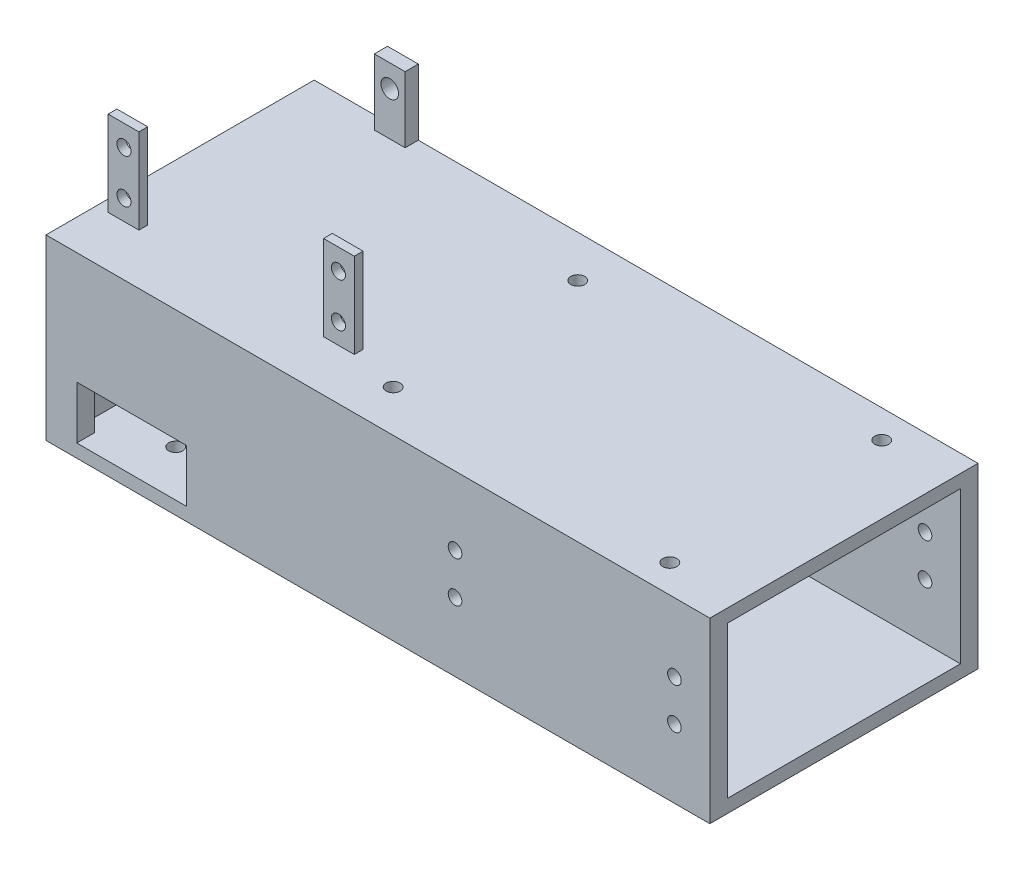
SolidWorks part; units mm, degrees
ref_plane "정면" through (0, 0, 0) normal (0, 0, 1) x (1, 0, 0)
ref_plane "윗면" through (0, 0, 0) normal (0, 1, 0) x (1, 0, 0)
ref_plane "우측면" through (0, 0, 0) normal (1, 0, 0) x (0, 0, -1)
sketch "Sketch1" plane through (0, 0, 0) normal (0, 1, 0) x (1, 0, 0)
  line L0 (-75.5, 30.5) -> (75.5, 30.5)
  line L1 (-71.5, 26.5) -> (71.5, 26.5)
  line L2 (-71.5, 26.5) -> (-71.5, -26.5)
  line L3 (-71.5, -26.5) -> (71.5, -26.5)
  line L4 (71.5, 26.5) -> (71.5, -26.5)
  line L5 (-71.5, 26.5) -> (71.5, -26.5) construction
  line L6 (-71.5, -26.5) -> (71.5, 26.5) construction
  line L7 (75.5, 30.5) -> (75.5, -30.5)
  line L8 (-75.5, -30.5) -> (75.5, -30.5)
  line L9 (-75.5, 30.5) -> (-75.5, -30.5)
  point P0 (0, 0)
  dimension "D1" = 143
  dimension "D2" = 53
  dimension "D3" = 4
extrude "Boss-Extrude1" add sketch "Sketch1" along normal mid plane 40.5
sketch "Sketch2" plane through (0, -20.25, 0) normal (0, -1, 0) x (1, 0, 0)
  line L1 (-71.5, 26.5) -> (71.5, 26.5)
  line L2 (-71.5, 26.5) -> (-71.5, -26.5)
  line L3 (-71.5, -26.5) -> (71.5, -26.5)
  line L4 (71.5, 26.5) -> (71.5, -26.5)
extrude "Boss-Extrude2" add sketch "Sketch2" against normal blind 3
sketch "Sketch7" plane through (75.5, 0, 0) normal (1, 0, 0) x (0, 0, -1)
  line L0 (-30.5, 20.25) -> (30.5, 20.25) construction
  line L1 (-26.5, 20.25) -> (26.5, 20.25)
  line L2 (-26.5, 20.25) -> (-26.5, -17.25)
  line L3 (-26.5, -17.25) -> (26.5, -17.25)
  line L4 (26.5, 20.25) -> (26.5, -17.25)
  line L6 (26.5, -17.25) -> (-26.5, -17.25) construction
  line L7 (26.5, -17.25) -> (-26.5, -17.25) construction
  point P7 (0, 20.25)
  dimension "D2" = 53
extrude "Cut-Extrude3" cut sketch "Sketch7" against normal blind 4 contours L4 L3 L2 L1
sketch "Sketch9" plane through (0, 20.25, 0) normal (0, 1, 0) x (1, 0, 0)
  line L0 (-71.5, -26.5) -> (-71.5, 26.5) construction
  line L1 (-71.5, 26.5) -> (75.5, 26.5) construction
  line L2 (75.5, -26.5) -> (-71.5, -26.5) construction
  line L3 (75.5, -26.5) -> (75.5, 26.5) construction
  line L4 (-71.5, -26.5) -> (-71.5, 26.5)
  line L5 (-71.5, 26.5) -> (75.5, 26.5)
  line L6 (75.5, -26.5) -> (-71.5, -26.5)
  line L7 (75.5, -26.5) -> (75.5, 26.5)
extrude "Boss-Extrude3" add sketch "Sketch9" against normal blind 3
sketch "Sketch10" plane through (0, 20.25, 0) normal (0, 1, 0) x (1, 0, 0)
  line L0 (-75.5, 0) -> (75.5, 0) construction
  line L1 (-75.5, 30.5) -> (-75.5, -30.5) construction
  line L2 (75.5, -30.5) -> (75.5, 30.5) construction
  line L3 (60, 0) -> (60, 24.1) construction
  line L4 (-6.04, 0) -> (-6.04, 21) construction
  circle A0 centre (60, 24.1) radius 1.6
  circle A1 centre (60, -24.1) radius 1.6
  circle A2 centre (-6.04, 21) radius 1.6
  circle A3 centre (-6.04, -21) radius 1.6
  dimension "D2" = 3.2
  dimension "D5" = 3.2
  dimension "D1" = 24.1
  dimension "D3" = 15.5
  dimension "D4" = 21
  dimension "D6" = 66.04
extrude "Cut-Extrude4" cut sketch "Sketch10" against normal up to next
sketch "Sketch12" plane through (0, 0, 30.5) normal (0, 0, 1) x (1, 0, 0)
  line L0 (75.5, 0) -> (-31.9096, 0) construction
  line L1 (75.5, 20.25) -> (75.5, -20.25) construction
  line L2 (67.4452, 4.65) -> (67.4452, -4.65) construction
  line L3 (67.4452, 4.65) -> (17.5452, 4.65) construction
  circle A0 centre (67.4452, 4.65) radius 1.55
  circle A1 centre (67.4452, -4.65) radius 1.55
  circle A2 centre (17.5452, 4.65) radius 1.55
  circle A3 centre (17.5452, -4.65) radius 1.55
  point P7 (67.4452, 0)
  dimension "D2" = 49.9
  dimension "D3" = 3.1
  dimension "D4" = 3.1
  dimension "D1" = 9.3
extrude "Cut-Extrude6" cut sketch "Sketch12" against normal through all
ref_plane "Plane1" through (0, 0, 17) normal (0, 0, 1) x (1, 0, 0)
sketch "Sketch13" plane through (0, 0, 17) normal (0, 0, 1) x (1, 0, 0)
  line L0 (-75.5, 20.25) -> (-75.5, -20.25) construction
  line L1 (-72.87, 20.25) -> (-65.87, 20.25)
  line L2 (-72.87, 20.25) -> (-72.87, 39.61)
  line L3 (-72.87, 39.61) -> (-65.87, 39.61)
  line L4 (-65.87, 20.25) -> (-65.87, 39.61)
  line L6 (-75.5, 20.25) -> (75.5, 20.25) construction
  dimension "D1" = 2.63
  dimension "D2" = 7
  dimension "D3" = 19.36
extrude "Boss-Extrude4" add sketch "Sketch13" along normal blind 2
sketch "Sketch16" plane through (0, 0, 19) normal (0, 0, 1) x (1, 0, 0)
  line L0 (-69.2622, 20.25) -> (-69.2622, 39.61) construction
  line L3 (-75.5, 20.25) -> (75.5, 20.25) construction
  line L4 (-72.87, 20.25) -> (-65.87, 20.25) construction
  line L5 (-65.87, 39.61) -> (-72.87, 39.61) construction
  circle A0 centre (-69.2622, 24.85) radius 1.6
  circle A1 centre (-69.2622, 34.85) radius 1.6
  point P8 (-69.2622, 23.25)
  point P11 (-69.2622, 34.85)
  dimension "D1" = 3.2
  dimension "D4" = 3.2
  dimension "D2" = 3
  dimension "D3" = 10
extrude "Cut-Extrude7" cut sketch "Sketch16" against normal blind 10
ref_plane "Plane3" through (-65.87, 0, 0) normal (1, 0, 0) x (0, 0, -1)
ref_plane "Plane4" through (-44.87, 0, 0) normal (1, 0, 0) x (0, 0, -1)
mirror "Mirror1" about plane through (-44.87, 0, 0) normal (1, 0, 0) of "Cut-Extrude7", "Boss-Extrude4"
sketch "Sketch17" plane through (0, 0, -30.5) normal (0, 0, -1) x (-1, 0, 0)
  line L0 (-75.5, 20.25) -> (75.5, 20.25) construction
  line L1 (58.81, 20.25) -> (51.81, 20.25)
  line L2 (58.81, 20.25) -> (58.81, 35.25)
  line L3 (58.81, 35.25) -> (51.81, 35.25)
  line L4 (51.81, 20.25) -> (51.81, 35.25)
  line L5 (55.31, 20.25) -> (55.31, 35.25) construction
  line L6 (75.5, 20.25) -> (75.5, -20.25) construction
  circle A0 centre (55.31, 30.15) radius 2
  point P8 (55.31, 30.15)
  dimension "D2" = 4
  dimension "D1" = 9.9
  dimension "D3" = 20.19
  dimension "D4" = 7
  dimension "D5" = 15
extrude "Boss-Extrude5" add sketch "Sketch17" against normal blind 3
sketch "Sketch18" plane through (0, -20.25, 0) normal (0, -1, 0) x (1, 0, 0)
  line L0 (-56.5, 30.5) -> (-56.5, -30.5) construction
  line L1 (-75.5, 30.5) -> (75.5, 30.5) construction
  line L2 (75.5, -30.5) -> (-75.5, -30.5) construction
  line L3 (-75.5, 0) -> (75.5, 0) construction
  line L4 (-75.5, -30.5) -> (-75.5, 30.5) construction
  line L5 (75.5, 30.5) -> (75.5, -30.5) construction
  circle A0 centre (-56.5, 20) radius 1.6
  circle A1 centre (-56.5, -20) radius 1.6
  point P12 (-56.5, 20)
  point P13 (-56.5, -20)
  dimension "D3" = 19
  dimension "D1" = 20
  dimension "D2" = 20
extrude "Cut-Extrude8" cut sketch "Sketch18" against normal blind 10
sketch "Sketch19" plane through (0, 0, 30.5) normal (0, 0, 1) x (1, 0, 0)
  line L1 (-68.5, -17.25) -> (-43.5, -17.25)
  line L2 (-68.5, -17.25) -> (-68.5, -5.25)
  line L3 (-68.5, -5.25) -> (-43.5, -5.25)
  line L4 (-43.5, -17.25) -> (-43.5, -5.25)
  line L5 (-75.5, 20.25) -> (-75.5, -20.25) construction
  dimension "D1" = 7
  dimension "D2" = 25
  dimension "D3" = 12
extrude "Cut-Extrude9" cut sketch "Sketch19" against normal through all
